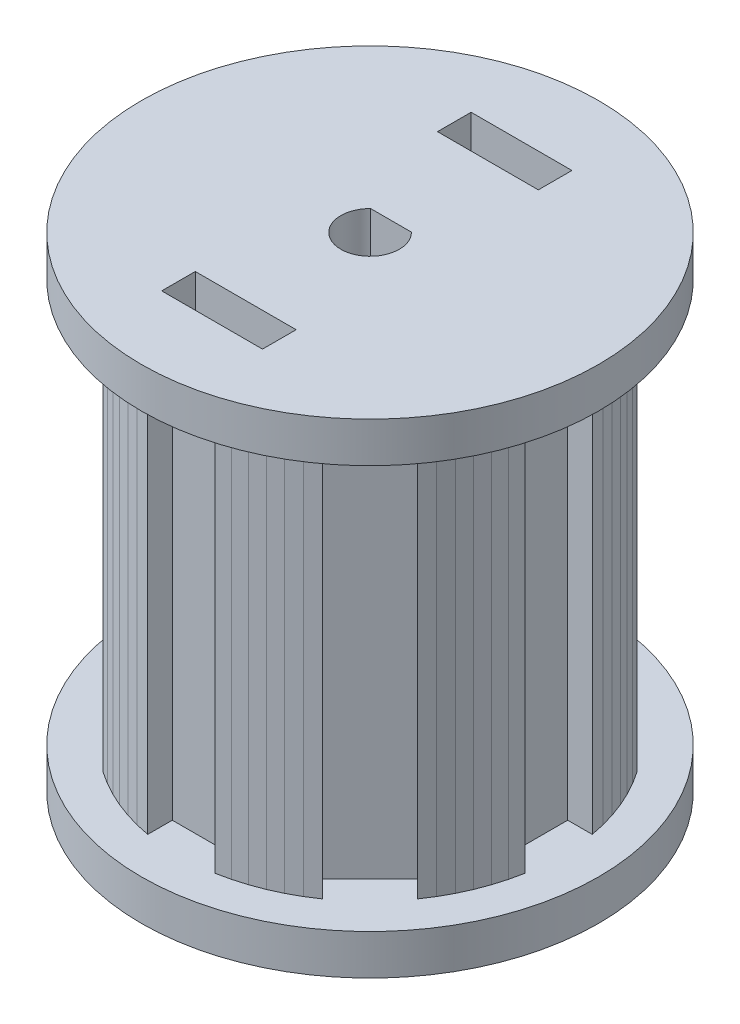
SolidWorks part; units mm, degrees
ref_plane "Front Plane" through (0, 0, 0) normal (0, 0, 1) x (1, 0, 0)
ref_plane "Top Plane" through (0, 0, 0) normal (0, 1, 0) x (1, 0, 0)
ref_plane "Right Plane" through (0, 0, 0) normal (1, 0, 0) x (0, 0, -1)
ref_plane "Plane1" through (0, -15, 0) normal (0, 1, 0) x (1, 0, 0)
ref_plane "Plane2" through (0, 21, 0) normal (0, 1, 0) x (1, 0, 0)
sketch "Sketch1" plane through (0, -15, 0) normal (0, 1, 0) x (1, 0, 0)
  circle A0 centre (0, 0) radius 17
  dimension "D1" = 34
extrude "Boss-Extrude1" add sketch "Sketch1" along normal blind 3
sketch "Sketch3" plane through (0, 21, 0) normal (0, 1, 0) x (1, 0, 0)
  circle A0 centre (0, 0) radius 17
  dimension "D1" = 34
extrude "Boss-Extrude2" add sketch "Sketch3" against normal blind 3 separate body
ref_plane "Plane3" through (0, -12, 0) normal (0, 1, 0) x (1, 0, 0)
sketch "Sketch6" plane through (0, -12, 0) normal (0, 1, 0) x (1, 0, 0)
  line L0 (-10.3961, -6.8606) -> (-11.6878, -8.1522)
  line L1 (-11.6878, -8.1522) -> (-12.2448, -7.2889)
  line L2 (-12.2448, -7.2889) -> (-12.7381, -6.3877)
  line L3 (-12.7381, -6.3877) -> (-13.1653, -5.4532)
  line L4 (-13.1653, -5.4532) -> (-13.524, -4.4905)
  line L5 (-13.524, -4.4905) -> (-13.8124, -3.5043)
  line L6 (-13.8124, -3.5043) -> (-14.029, -2.5)
  line L7 (-14.029, -2.5) -> (-12.2023, -2.5)
  line L8 (-12.2023, -2.5) -> (-12.2023, 2.5)
  line L9 (-12.2023, 2.5) -> (-14.029, 2.5)
  line L10 (-14.029, 2.5) -> (-13.8124, 3.5043)
  line L11 (-13.8124, 3.5043) -> (-13.524, 4.4905)
  line L12 (-13.524, 4.4905) -> (-13.1653, 5.4532)
  line L13 (-13.1653, 5.4532) -> (-12.7381, 6.3877)
  line L14 (-12.7381, 6.3877) -> (-12.2448, 7.2889)
  line L15 (-12.2448, 7.2889) -> (-11.6878, 8.1522)
  line L16 (-11.6878, 8.1522) -> (-10.3961, 6.8606)
  line L17 (-10.3961, 6.8606) -> (-6.8606, 10.3961)
  line L18 (-6.8606, 10.3961) -> (-8.1522, 11.6878)
  line L19 (-8.1522, 11.6878) -> (-7.2889, 12.2448)
  line L20 (-7.2889, 12.2448) -> (-6.3877, 12.7381)
  line L21 (-6.3877, 12.7381) -> (-5.4532, 13.1653)
  line L22 (-5.4532, 13.1653) -> (-4.4905, 13.524)
  line L23 (-4.4905, 13.524) -> (-3.5043, 13.8124)
  line L24 (-3.5043, 13.8124) -> (-2.5, 14.029)
  line L25 (-2.5, 14.029) -> (-2.5, 12.1742)
  line L26 (-2.5, 12.1742) -> (2.5, 12.2023)
  line L27 (2.5, 12.2023) -> (2.5, 14.029)
  line L28 (2.5, 14.029) -> (3.5043, 13.8124)
  line L29 (3.5043, 13.8124) -> (4.4905, 13.524)
  line L30 (4.4905, 13.524) -> (5.4532, 13.1653)
  line L31 (5.4532, 13.1653) -> (6.3877, 12.7381)
  line L32 (6.3877, 12.7381) -> (7.2889, 12.2448)
  line L33 (7.2889, 12.2448) -> (8.1522, 11.6878)
  line L34 (8.1522, 11.6878) -> (6.8606, 10.3961)
  line L35 (6.8606, 10.3961) -> (10.3961, 6.8606)
  line L36 (10.3961, 6.8606) -> (11.6878, 8.1522)
  line L37 (11.6878, 8.1522) -> (12.2448, 7.2889)
  line L38 (12.2448, 7.2889) -> (12.7381, 6.3877)
  line L39 (12.7381, 6.3877) -> (13.1653, 5.4532)
  line L40 (13.1653, 5.4532) -> (13.524, 4.4905)
  line L41 (13.524, 4.4905) -> (13.8124, 3.5043)
  line L42 (13.8124, 3.5043) -> (14.029, 2.5)
  line L43 (14.029, 2.5) -> (12.2023, 2.5)
  line L44 (12.2023, 2.5) -> (12.2023, -2.5)
  line L45 (12.2023, -2.5) -> (14.029, -2.5)
  line L46 (14.029, -2.5) -> (13.8124, -3.5043)
  line L47 (13.8124, -3.5043) -> (13.524, -4.4905)
  line L48 (13.524, -4.4905) -> (13.1653, -5.4532)
  line L49 (13.1653, -5.4532) -> (12.7381, -6.3877)
  line L50 (12.7381, -6.3877) -> (12.2448, -7.2889)
  line L51 (12.2448, -7.2889) -> (11.6878, -8.1522)
  line L52 (11.6878, -8.1522) -> (10.3961, -6.8606)
  line L53 (10.3961, -6.8606) -> (6.8606, -10.3961)
  line L54 (6.8606, -10.3961) -> (8.1522, -11.6878)
  line L55 (8.1522, -11.6878) -> (7.2889, -12.2448)
  line L56 (7.2889, -12.2448) -> (6.3877, -12.7381)
  line L57 (6.3877, -12.7381) -> (5.4532, -13.1653)
  line L58 (5.4532, -13.1653) -> (4.4905, -13.524)
  line L59 (4.4905, -13.524) -> (3.5043, -13.8124)
  line L60 (3.5043, -13.8124) -> (2.5, -14.029)
  line L61 (2.5, -14.029) -> (2.5, -12.2023)
  line L62 (2.5, -12.2023) -> (-2.5, -12.2023)
  line L63 (-2.5, -12.2023) -> (-2.5, -14.029)
  line L64 (-2.5, -14.029) -> (-3.5043, -13.8124)
  line L65 (-3.5043, -13.8124) -> (-4.4905, -13.524)
  line L66 (-4.4905, -13.524) -> (-5.4532, -13.1653)
  line L67 (-5.4532, -13.1653) -> (-6.3877, -12.7381)
  line L68 (-6.3877, -12.7381) -> (-7.2889, -12.2448)
  line L69 (-7.2889, -12.2448) -> (-8.1522, -11.6878)
  line L70 (-8.1522, -11.6878) -> (-6.8606, -10.3961)
  line L71 (-6.8606, -10.3961) -> (-10.3961, -6.8606)
extrude "Boss-Extrude3" add sketch "Sketch6" along normal blind 31
sketch "Sketch7" plane through (-0.0686, 0, -12.1878) normal (-0.0056, 0, -1) x (-1, 0, 0.0056)
  line L0 (2.5686, 18) -> (-2.4313, 18) construction
  circle A0 centre (-0.1208, 16) radius 1.7514
  dimension "D1" = 2
extrude "Cut-Extrude11" cut sketch "Sketch7" against normal blind 50
sketch "Sketch2" plane through (0, -15, 0) normal (0, 1, 0) x (1, 0, 0)
  line L0 (1.5148, 1.5664) -> (-1.5212, 1.5664)
  arc A0 (1.5148, 1.5664) -> (-1.5212, 1.5664) centre (-0.0032, 0.0099) cw
extrude "Cut-Extrude1" cut sketch "Sketch2" along normal blind 50
sketch "Sketch8" plane through (0, -15, 0) normal (0, 1, 0) x (1, 0, 0)
  line L1 (-3.9871, 11.5054) -> (3.5129, 11.5054)
  line L2 (-3.9871, 11.5054) -> (-3.9871, 9.0054)
  line L3 (-3.9871, 9.0054) -> (3.5129, 9.0054)
  line L4 (3.5129, 11.5054) -> (3.5129, 9.0054)
  dimension "D1" = 7.5
  dimension "D2" = 2.5
extrude "Cut-Extrude12" cut sketch "Sketch8" along normal blind 40
ref_plane "Plane4" through (0, 0, 0) normal (0, 0, 1) x (1, 0, 0)
ref_plane "Plane5" through (0, 0, 0) normal (1, 0, 0) x (0, 0, -1)
mirror "Mirror1" about plane through (0, 0, 0) normal (0, 0, 1) of "Cut-Extrude12"
sketch "Sketch9" plane through (0, 21, 0) normal (0, 1, 0) x (1, 0, 0)
  circle A0 centre (0, 0) radius 17
  circle A1 centre (0, 0) radius 16
  dimension "D1" = 34
  dimension "D2" = 1
